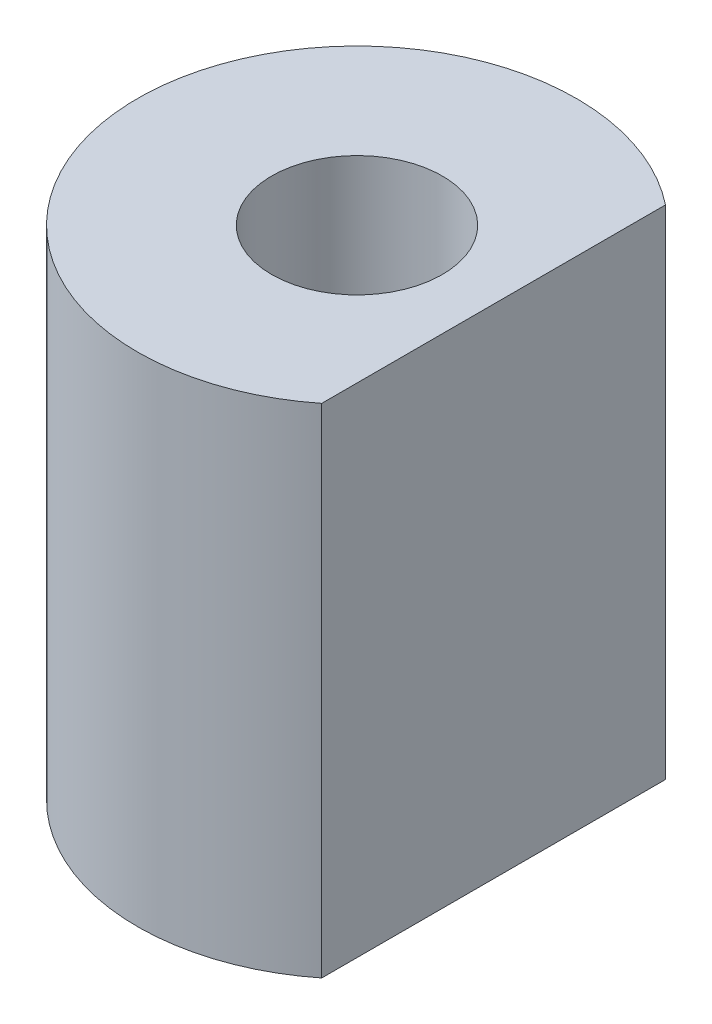
SolidWorks part; units mm, degrees
ref_plane "前视基准面" through (0, 0, 0) normal (0, 0, 1) x (1, 0, 0)
ref_plane "上视基准面" through (0, 0, 0) normal (0, 1, 0) x (1, 0, 0)
ref_plane "右视基准面" through (0, 0, 0) normal (1, 0, 0) x (0, 0, -1)
other "Configuration Table"
sketch "草图2" plane through (0, 0, 0) normal (0, 1, 0) x (1, 0, 0)
  line L0 (2.8, 3.5228) -> (2.8, -3.5228)
  circle A18 centre (0, 0) radius 4.5
  circle A19 centre (0, 0) radius 1.75
  dimension "D1" = 3.5
  dimension "D2" = 9
  dimension "D3" = 2.8
extrude "凸台-拉伸1" add sketch "草图2" along normal blind 10.2 contours L0 A18 A19
